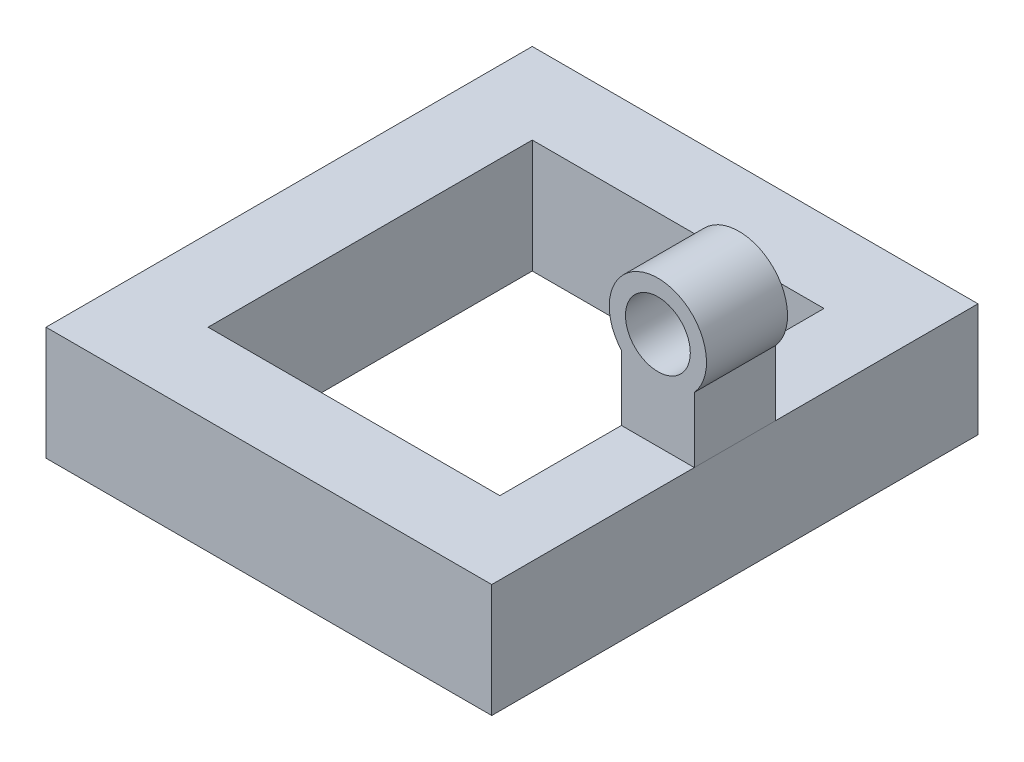
SolidWorks part; units mm, degrees
ref_plane "前视基准面" through (0, 0, 0) normal (0, 0, 1) x (1, 0, 0)
ref_plane "上视基准面" through (0, 0, 0) normal (0, 1, 0) x (1, 0, 0)
ref_plane "右视基准面" through (0, 0, 0) normal (1, 0, 0) x (0, 0, -1)
other "Configuration Table"
sketch "草图1" plane through (0, 0, 0) normal (0, 1, 0) x (1, 0, 0)
  line L0 (0, 0) -> (55, 0)
  line L1 (55, 0) -> (55, 60)
  line L2 (55, 60) -> (0, 60)
  line L3 (0, 60) -> (0, 0)
extrude "凸台-拉伸1" add sketch "草图1" along normal blind 14
sketch "草图5" plane through (0, 0, 0) normal (0, 1, 0) x (1, 0, 0)
  line L3 (10, 10) -> (10, 50)
  line L4 (10, 50) -> (46, 50)
  line L5 (46, 50) -> (46, 10)
  line L6 (46, 10) -> (10, 10)
extrude "切除-拉伸1" cut sketch "草图5" along normal blind 15 contours L3 L4 L5 L6
sketch "草图7" plane through (0, 0, 0) normal (0, 0, 1) x (1, 0, 0)
  line L0 (55, 14) -> (50.5, 14)
  line L3 (55, 14) -> (55, 22.0314)
  line L4 (50.5, 14) -> (46, 14)
  line L5 (46, 14) -> (46, 22.0314)
  arc A1 (55, 22.0314) -> (46, 22.0314) centre (50.5, 26) ccw
  circle A2 centre (50.5, 26) radius 4
extrude "凸台-拉伸2" add sketch "草图7" along normal blind 10 from offset 35 separate body
